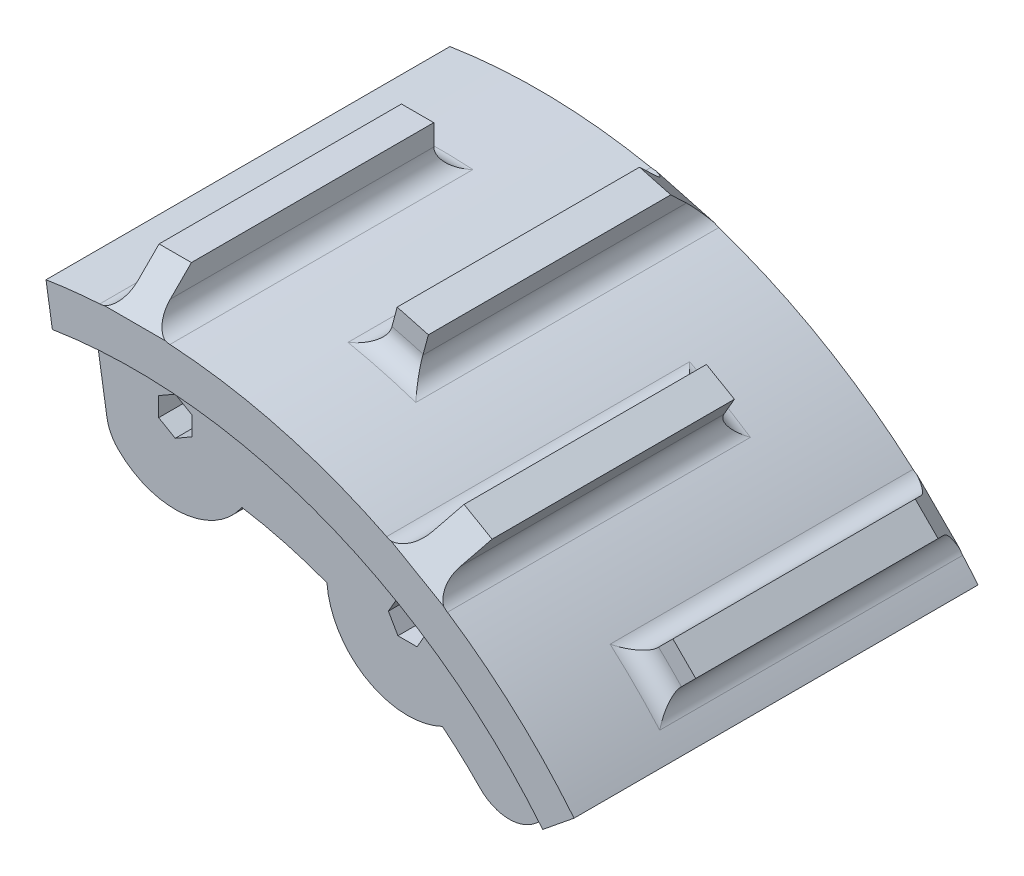
SolidWorks part; units mm, degrees
ref_plane "前视基准面" through (0, 0, 0) normal (0, 0, 1) x (1, 0, 0)
ref_plane "上视基准面" through (0, 0, 0) normal (0, 1, 0) x (1, 0, 0)
ref_plane "右视基准面" through (0, 0, 0) normal (1, 0, 0) x (0, 0, -1)
other "Configuration Table"
sketch "草图1" plane through (0, 0, 0) normal (0, 0, 1) x (1, 0, 0)
  circle A0 centre (0, 0) radius 140
  dimension "D1" = 280
extrude "凸台-拉伸1" add sketch "草图1" along normal blind 100
sketch "草图2" plane through (0, 0, 100) normal (0, 0, 1) x (1, 0, 0)
  circle A0 centre (0, 0) radius 105
  dimension "D1" = 210
extrude "切除-拉伸1" cut sketch "草图2" against normal blind 100
sketch "草图3" plane through (0, 0, 100) normal (0, 0, 1) x (1, 0, 0)
  circle A0 centre (0, 0) radius 115 construction
  circle A1 centre (0, 115) radius 20
  circle A2 centre (57.5, 99.5929) radius 20
  circle A3 centre (99.5929, 57.5) radius 20
  circle A4 centre (115, 0) radius 20
  circle A5 centre (99.5929, -57.5) radius 20
  circle A6 centre (57.5, -99.5929) radius 20
  circle A7 centre (0, -115) radius 20
  circle A8 centre (-57.5, -99.5929) radius 20
  circle A9 centre (-99.5929, -57.5) radius 20
  circle A10 centre (-115, 0) radius 20
  circle A11 centre (-99.5929, 57.5) radius 20
  circle A12 centre (-57.5, 99.5929) radius 20
  point P30 (0, 0)
  dimension "D1" = 230
  dimension "D2" = 40
  dimension "D3" = 12
extrude "凸台-拉伸2" add sketch "草图3" against normal through all
sketch "草图4" plane through (0, 0, 100) normal (0, 0, 1) x (1, 0, 0)
  circle A0 centre (0, 0) radius 130
  dimension "D1" = 260
extrude "切除-拉伸2" cut sketch "草图4" against normal blind 10
sketch "草图5" plane through (0, 0, 0) normal (0, 0, -1) x (-1, 0, 0)
  circle A1 centre (0, 0) radius 130
  circle A2 centre (0, 0) radius 130
  dimension "D1" = 0
extrude "切除-拉伸3" cut sketch "草图5" against normal blind 10
sketch "草图6" plane through (0, 0, 90) normal (0, 0, 1) x (1, 0, 0)
  line L0 (55.1329, 95.4929) -> (59.8671, 95.4929)
  line L1 (0, 110.2657) -> (4.1, 112.6329)
  line L2 (4.1, 112.6329) -> (4.1, 117.3671)
  line L3 (4.1, 117.3671) -> (0, 119.7343)
  line L4 (0, 119.7343) -> (-4.1, 117.3671)
  line L5 (-4.1, 117.3671) -> (-4.1, 112.6329)
  line L6 (-4.1, 112.6329) -> (0, 110.2657)
  line L7 (59.8671, 95.4929) -> (62.2343, 99.5929)
  line L8 (62.2343, 99.5929) -> (59.8671, 103.6929)
  line L9 (59.8671, 103.6929) -> (55.1329, 103.6929)
  line L10 (55.1329, 103.6929) -> (52.7657, 99.5929)
  line L11 (52.7657, 99.5929) -> (55.1329, 95.4929)
  line L12 (95.4929, 55.1329) -> (99.5929, 52.7657)
  line L13 (99.5929, 52.7657) -> (103.6929, 55.1329)
  line L14 (103.6929, 55.1329) -> (103.6929, 59.8671)
  line L15 (103.6929, 59.8671) -> (99.5929, 62.2343)
  line L16 (99.5929, 62.2343) -> (95.4929, 59.8671)
  line L17 (95.4929, 59.8671) -> (95.4929, 55.1329)
  line L18 (110.2657, 0) -> (112.6329, -4.1)
  line L19 (112.6329, -4.1) -> (117.3671, -4.1)
  line L20 (117.3671, -4.1) -> (119.7343, 0)
  line L21 (119.7343, 0) -> (117.3671, 4.1)
  line L22 (117.3671, 4.1) -> (112.6329, 4.1)
  line L23 (112.6329, 4.1) -> (110.2657, 0)
  line L24 (95.4929, -55.1329) -> (95.4929, -59.8671)
  line L25 (95.4929, -59.8671) -> (99.5929, -62.2343)
  line L26 (99.5929, -62.2343) -> (103.6929, -59.8671)
  line L27 (103.6929, -59.8671) -> (103.6929, -55.1329)
  line L28 (103.6929, -55.1329) -> (99.5929, -52.7657)
  line L29 (99.5929, -52.7657) -> (95.4929, -55.1329)
  line L30 (55.1329, -95.4929) -> (52.7657, -99.5929)
  line L31 (52.7657, -99.5929) -> (55.1329, -103.6929)
  line L32 (55.1329, -103.6929) -> (59.8671, -103.6929)
  line L33 (59.8671, -103.6929) -> (62.2343, -99.5929)
  line L34 (62.2343, -99.5929) -> (59.8671, -95.4929)
  line L35 (59.8671, -95.4929) -> (55.1329, -95.4929)
  line L36 (0, -110.2657) -> (-4.1, -112.6329)
  line L37 (-4.1, -112.6329) -> (-4.1, -117.3671)
  line L38 (-4.1, -117.3671) -> (0, -119.7343)
  line L39 (0, -119.7343) -> (4.1, -117.3671)
  line L40 (4.1, -117.3671) -> (4.1, -112.6329)
  line L41 (4.1, -112.6329) -> (0, -110.2657)
  line L42 (-55.1329, -95.4929) -> (-59.8671, -95.4929)
  line L43 (-59.8671, -95.4929) -> (-62.2343, -99.5929)
  line L44 (-62.2343, -99.5929) -> (-59.8671, -103.6929)
  line L45 (-59.8671, -103.6929) -> (-55.1329, -103.6929)
  line L46 (-55.1329, -103.6929) -> (-52.7657, -99.5929)
  line L47 (-52.7657, -99.5929) -> (-55.1329, -95.4929)
  line L48 (-95.4929, -55.1329) -> (-99.5929, -52.7657)
  line L49 (-99.5929, -52.7657) -> (-103.6929, -55.1329)
  line L50 (-103.6929, -55.1329) -> (-103.6929, -59.8671)
  line L51 (-103.6929, -59.8671) -> (-99.5929, -62.2343)
  line L52 (-99.5929, -62.2343) -> (-95.4929, -59.8671)
  line L53 (-95.4929, -59.8671) -> (-95.4929, -55.1329)
  line L54 (-110.2657, 0) -> (-112.6329, 4.1)
  line L55 (-112.6329, 4.1) -> (-117.3671, 4.1)
  line L56 (-117.3671, 4.1) -> (-119.7343, 0)
  line L57 (-119.7343, 0) -> (-117.3671, -4.1)
  line L58 (-117.3671, -4.1) -> (-112.6329, -4.1)
  line L59 (-112.6329, -4.1) -> (-110.2657, 0)
  line L60 (-95.4929, 55.1329) -> (-95.4929, 59.8671)
  line L61 (-95.4929, 59.8671) -> (-99.5929, 62.2343)
  line L62 (-99.5929, 62.2343) -> (-103.6929, 59.8671)
  line L63 (-103.6929, 59.8671) -> (-103.6929, 55.1329)
  line L64 (-103.6929, 55.1329) -> (-99.5929, 52.7657)
  line L65 (-99.5929, 52.7657) -> (-95.4929, 55.1329)
  line L66 (-55.1329, 95.4929) -> (-52.7657, 99.5929)
  line L67 (-52.7657, 99.5929) -> (-55.1329, 103.6929)
  line L68 (-55.1329, 103.6929) -> (-59.8671, 103.6929)
  line L69 (-59.8671, 103.6929) -> (-62.2343, 99.5929)
  line L70 (-62.2343, 99.5929) -> (-59.8671, 95.4929)
  line L71 (-59.8671, 95.4929) -> (-55.1329, 95.4929)
  circle A0 centre (0, 115) radius 4.1 construction
  circle A1 centre (57.5, 99.5929) radius 4.1 construction
  circle A2 centre (99.5929, 57.5) radius 4.1 construction
  circle A3 centre (115, 0) radius 4.1 construction
  circle A4 centre (99.5929, -57.5) radius 4.1 construction
  circle A5 centre (57.5, -99.5929) radius 4.1 construction
  circle A6 centre (0, -115) radius 4.1 construction
  circle A7 centre (-57.5, -99.5929) radius 4.1 construction
  circle A8 centre (-99.5929, -57.5) radius 4.1 construction
  circle A9 centre (-115, 0) radius 4.1 construction
  circle A10 centre (-99.5929, 57.5) radius 4.1 construction
  circle A11 centre (-57.5, 99.5929) radius 4.1 construction
  point P100 (0, 0)
  dimension "D1" = 8.2
  dimension "D2" = 12
extrude "切除-拉伸4" cut sketch "草图6" against normal through all
sketch "草图7" plane through (0, 0, 100) normal (0, 0, 1) x (1, 0, 0)
  line L0 (0, 0) -> (0, 139.9428) construction
  line L1 (66.5073, 123.1941) -> (73.4355, 119.1941)
  line L2 (-4, 139.9428) -> (4, 139.9428)
  line L3 (-4, 139.9428) -> (-4, 149.9428)
  line L4 (-4, 149.9428) -> (4, 149.9428)
  line L5 (4, 139.9428) -> (4, 149.9428)
  line L6 (73.4355, 119.1941) -> (78.4355, 127.8543)
  line L7 (66.5073, 123.1941) -> (71.5073, 131.8543)
  line L8 (71.5073, 131.8543) -> (78.4355, 127.8543)
  line L9 (119.1941, 73.4355) -> (123.1941, 66.5073)
  line L10 (123.1941, 66.5073) -> (131.8543, 71.5073)
  line L11 (119.1941, 73.4355) -> (127.8543, 78.4355)
  line L12 (127.8543, 78.4355) -> (131.8543, 71.5073)
  line L13 (139.9428, 4) -> (139.9428, -4)
  line L14 (139.9428, -4) -> (149.9428, -4)
  line L15 (139.9428, 4) -> (149.9428, 4)
  line L16 (149.9428, 4) -> (149.9428, -4)
  line L17 (123.1941, -66.5073) -> (119.1941, -73.4355)
  line L18 (119.1941, -73.4355) -> (127.8543, -78.4355)
  line L19 (123.1941, -66.5073) -> (131.8543, -71.5073)
  line L20 (131.8543, -71.5073) -> (127.8543, -78.4355)
  line L21 (73.4355, -119.1941) -> (66.5073, -123.1941)
  line L22 (66.5073, -123.1941) -> (71.5073, -131.8543)
  line L23 (73.4355, -119.1941) -> (78.4355, -127.8543)
  line L24 (78.4355, -127.8543) -> (71.5073, -131.8543)
  line L25 (4, -139.9428) -> (-4, -139.9428)
  line L26 (-4, -139.9428) -> (-4, -149.9428)
  line L27 (4, -139.9428) -> (4, -149.9428)
  line L28 (4, -149.9428) -> (-4, -149.9428)
  line L29 (-66.5073, -123.1941) -> (-73.4355, -119.1941)
  line L30 (-73.4355, -119.1941) -> (-78.4355, -127.8543)
  line L31 (-66.5073, -123.1941) -> (-71.5073, -131.8543)
  line L32 (-71.5073, -131.8543) -> (-78.4355, -127.8543)
  line L33 (-119.1941, -73.4355) -> (-123.1941, -66.5073)
  line L34 (-123.1941, -66.5073) -> (-131.8543, -71.5073)
  line L35 (-119.1941, -73.4355) -> (-127.8543, -78.4355)
  line L36 (-127.8543, -78.4355) -> (-131.8543, -71.5073)
  line L37 (-139.9428, -4) -> (-139.9428, 4)
  line L38 (-139.9428, 4) -> (-149.9428, 4)
  line L39 (-139.9428, -4) -> (-149.9428, -4)
  line L40 (-149.9428, -4) -> (-149.9428, 4)
  line L41 (-123.1941, 66.5073) -> (-119.1941, 73.4355)
  line L42 (-119.1941, 73.4355) -> (-127.8543, 78.4355)
  line L43 (-123.1941, 66.5073) -> (-131.8543, 71.5073)
  line L44 (-131.8543, 71.5073) -> (-127.8543, 78.4355)
  line L45 (-73.4355, 119.1941) -> (-66.5073, 123.1941)
  line L46 (-66.5073, 123.1941) -> (-71.5073, 131.8543)
  line L47 (-73.4355, 119.1941) -> (-78.4355, 127.8543)
  line L48 (-78.4355, 127.8543) -> (-71.5073, 131.8543)
  circle A1 centre (0, 0) radius 140 construction
  point P57 (0, 0)
  dimension "D1" = 10
  dimension "D2" = 8
  dimension "D3" = 12
extrude "凸台-拉伸3" add sketch "草图7" against normal blind 70
sketch "草图9" plane through (0, 0, 0) normal (0, 0, -1) x (-1, 0, 0)
  line L0 (0, 0) -> (0, 140) construction
  line L1 (0, 0) -> (36.2199, 135.1744) construction
  line L2 (34.9444, 145.8689) -> (32.3562, 136.2097)
  line L3 (32.3562, 136.2097) -> (40.0836, 134.1391)
  line L4 (40.0836, 134.1391) -> (42.6718, 143.7984)
  line L5 (42.6718, 143.7984) -> (34.9444, 145.8689)
  line L6 (101.783, 96.1261) -> (108.854, 103.1972)
  line L7 (108.854, 103.1972) -> (103.1972, 108.854)
  line L8 (103.1972, 108.854) -> (96.1261, 101.783)
  line L9 (96.1261, 101.783) -> (101.783, 96.1261)
  line L10 (136.2097, 32.3562) -> (145.8689, 34.9444)
  line L11 (145.8689, 34.9444) -> (143.7984, 42.6718)
  line L12 (143.7984, 42.6718) -> (134.1391, 40.0836)
  line L13 (134.1391, 40.0836) -> (136.2097, 32.3562)
  line L14 (134.1391, -40.0836) -> (143.7984, -42.6718)
  line L15 (143.7984, -42.6718) -> (145.8689, -34.9444)
  line L16 (145.8689, -34.9444) -> (136.2097, -32.3562)
  line L17 (136.2097, -32.3562) -> (134.1391, -40.0836)
  line L18 (96.1261, -101.783) -> (103.1972, -108.854)
  line L19 (103.1972, -108.854) -> (108.854, -103.1972)
  line L20 (108.854, -103.1972) -> (101.783, -96.1261)
  line L21 (101.783, -96.1261) -> (96.1261, -101.783)
  line L22 (32.3562, -136.2097) -> (34.9444, -145.8689)
  line L23 (34.9444, -145.8689) -> (42.6718, -143.7984)
  line L24 (42.6718, -143.7984) -> (40.0836, -134.1391)
  line L25 (40.0836, -134.1391) -> (32.3562, -136.2097)
  line L26 (-40.0836, -134.1391) -> (-42.6718, -143.7984)
  line L27 (-42.6718, -143.7984) -> (-34.9444, -145.8689)
  line L28 (-34.9444, -145.8689) -> (-32.3562, -136.2097)
  line L29 (-32.3562, -136.2097) -> (-40.0836, -134.1391)
  line L30 (-101.783, -96.1261) -> (-108.854, -103.1972)
  line L31 (-108.854, -103.1972) -> (-103.1972, -108.854)
  line L32 (-103.1972, -108.854) -> (-96.1261, -101.783)
  line L33 (-96.1261, -101.783) -> (-101.783, -96.1261)
  line L34 (-136.2097, -32.3562) -> (-145.8689, -34.9444)
  line L35 (-145.8689, -34.9444) -> (-143.7984, -42.6718)
  line L36 (-143.7984, -42.6718) -> (-134.1391, -40.0836)
  line L37 (-134.1391, -40.0836) -> (-136.2097, -32.3562)
  line L38 (-134.1391, 40.0836) -> (-143.7984, 42.6718)
  line L39 (-143.7984, 42.6718) -> (-145.8689, 34.9444)
  line L40 (-145.8689, 34.9444) -> (-136.2097, 32.3562)
  line L41 (-136.2097, 32.3562) -> (-134.1391, 40.0836)
  line L42 (-96.1261, 101.783) -> (-103.1972, 108.854)
  line L43 (-103.1972, 108.854) -> (-108.854, 103.1972)
  line L44 (-108.854, 103.1972) -> (-101.783, 96.1261)
  line L45 (-101.783, 96.1261) -> (-96.1261, 101.783)
  line L46 (-32.3562, 136.2097) -> (-34.9444, 145.8689)
  line L47 (-34.9444, 145.8689) -> (-42.6718, 143.7984)
  line L48 (-42.6718, 143.7984) -> (-40.0836, 134.1391)
  line L49 (-40.0836, 134.1391) -> (-32.3562, 136.2097)
  arc A0 (4, 139.9428) -> (-4, 139.9428) centre (0, 0) ccw construction
  circle A2 centre (0, 0) radius 140 construction
  point P60 (0, 0)
  dimension "D1" = 15
  dimension "D2" = 8
  dimension "D3" = 10
  dimension "D4" = 12
extrude "凸台-拉伸4" add sketch "草图9" against normal blind 70
fillet "圆角3" radius 5 72 edges at (123.1941, -66.5073, 65) (121.2436, -70, 30) (119.1941, -73.4355, 65) (101.783, -96.1261, 35) (98.9949, -98.9949, 70) (73.4355, -119.1941, 65) (70, -121.2436, 30) (40.0836, -134.1391, 35) (36.2347, -135.2296, 70) (32.3562, -136.2097, 35) (66.5073, -123.1941, 65) (96.1261, -101.783, 35) (4, -139.9428, 65) (0, -140, 30) (-4, -139.9428, 65) (-32.3562, -136.2097, 35) (-36.2347, -135.2296, 70) (-40.0836, -134.1391, 35) (-66.5073, -123.1941, 65) (-70, -121.2436, 30) (-73.4355, -119.1941, 65) (-96.1261, -101.783, 35) (-98.9949, -98.9949, 70) (-101.783, -96.1261, 35) (-119.1941, -73.4355, 65) (-121.2436, -70, 30) (-123.1941, -66.5073, 65) (-134.1391, -40.0836, 35) (-135.2296, -36.2347, 70) (-136.2097, -32.3562, 35) (-139.9428, -4, 65) (-140, 0, 30) (-139.9428, 4, 65) (-136.2097, 32.3562, 35) (-135.2296, 36.2347, 70) (-134.1391, 40.0836, 35) (-123.1941, 66.5073, 65) (-121.2436, 70, 30) (-119.1941, 73.4355, 65) (-101.783, 96.1261, 35) (-98.9949, 98.9949, 70) (-96.1261, 101.783, 35) (-73.4355, 119.1941, 65) (-70, 121.2436, 30) (-66.5073, 123.1941, 65) (-40.0836, 134.1391, 35) (-36.2347, 135.2296, 70) (-32.3562, 136.2097, 35) (-4, 139.9428, 65) (0, 140, 30) (4, 139.9428, 65) (32.3562, 136.2097, 35) (36.2347, 135.2296, 70) (40.0836, 134.1391, 35) (66.5073, 123.1941, 65) (70, 121.2436, 30) (73.4355, 119.1941, 65) (119.1941, 73.4355, 65) (121.2436, 70, 30) (123.1941, 66.5073, 65) (139.9428, 4, 65) (140, 0, 30) (139.9428, -4, 65) (96.1261, 101.783, 35) (98.9949, 98.9949, 70) (101.783, 96.1261, 35) (134.1391, 40.0836, 35) (135.2296, 36.2347, 70) (136.2097, 32.3562, 35) (136.2097, -32.3562, 35) (135.2296, -36.2347, 70) (134.1391, -40.0836, 35)
chamfer "倒角1" distance 10 angle 45 24 edges at (74.9714, 129.8543, 100) (106.0256, 106.0256, 0) (129.8543, 74.9714, 100) (144.8337, 38.8081, 0) (149.9428, 0, 100) (144.8337, -38.8081, 0) (129.8543, -74.9714, 100) (106.0256, -106.0256, 0) (74.9714, -129.8543, 100) (38.8081, -144.8337, 0) (0, -149.9428, 100) (-38.8081, -144.8337, 0) (-74.9714, -129.8543, 100) (-106.0256, -106.0256, 0) (-129.8543, -74.9714, 100) (-144.8337, -38.8081, 0) (-149.9428, 0, 100) (-129.8543, 74.9714, 100) (-74.9714, 129.8543, 100) (0, 149.9428, 100) (-144.8337, 38.8081, 0) (-106.0256, 106.0256, 0) (-38.8081, 144.8337, 0) (38.8081, 144.8337, 0)
sketch "草图10" plane through (0, 0, 0) normal (0, 0, -1) x (-1, 0, 0)
  line L0 (0, 0) -> (25.9267, 162.9503)
  line L1 (0, 0) -> (-128.1557, 103.9284)
  line L2 (0, 0) -> (0, 165) construction
  arc A0 (-128.1557, 103.9284) -> (25.9267, 162.9503) centre (0, 0) ccw
  point P1 (0, 0)
  point P3 (0, 0)
  dimension "D1" = 330
  dimension "D3" = 60
extrude "切除-拉伸6" cut sketch "草图10" against normal through all
fillet "圆角4" radius 10 2 edges at (-16.4988, 103.6957, 50) (81.5536, 66.1362, 50)
